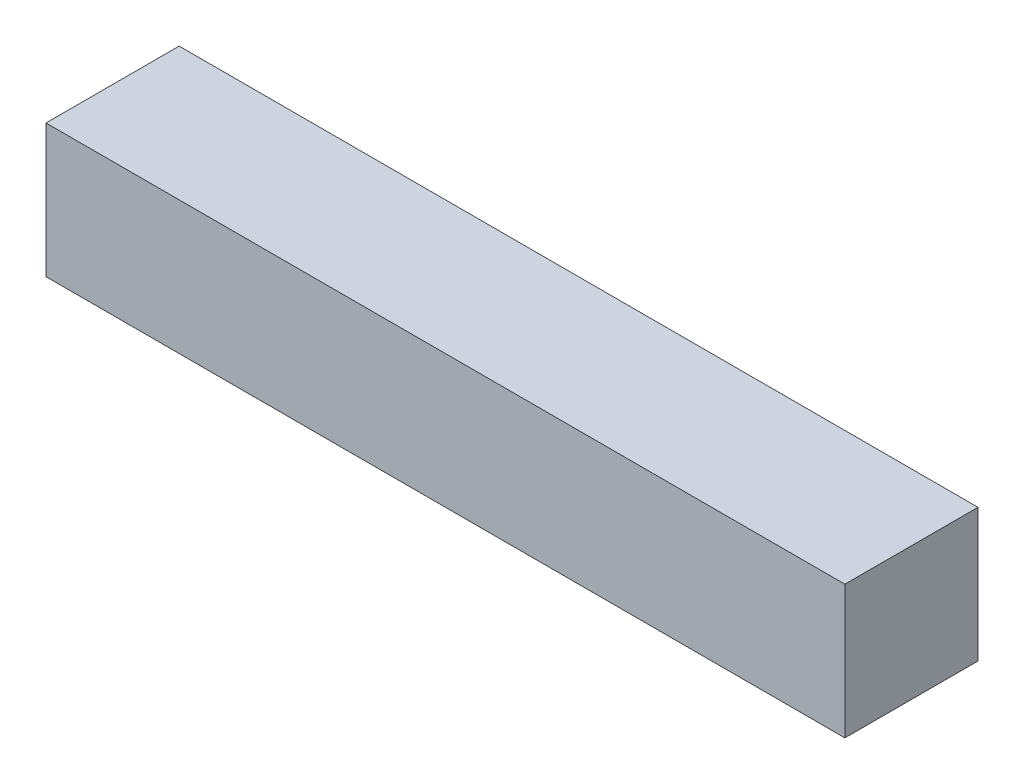
SolidWorks part; units mm, degrees
ref_plane "Front Plane" through (0, 0, 0) normal (0, 0, 1) x (1, 0, 0)
ref_plane "Top Plane" through (0, 0, 0) normal (0, 1, 0) x (1, 0, 0)
ref_plane "Right Plane" through (0, 0, 0) normal (1, 0, 0) x (0, 0, -1)
sketch "Sketch1" plane through (0, 0, 0) normal (0, 0, 1) x (1, 0, 0)
  line L0 (0, 10) -> (60, 10)
  line L1 (60, 10) -> (60, 0)
  line L2 (60, 0) -> (0, 0)
  line L3 (0, 10) -> (0, 0)
  point P2 (0, 0)
  dimension "D1" = 10
  dimension "D2" = 60
extrude "Boss-Extrude1" add sketch "Sketch1" along normal blind 10
